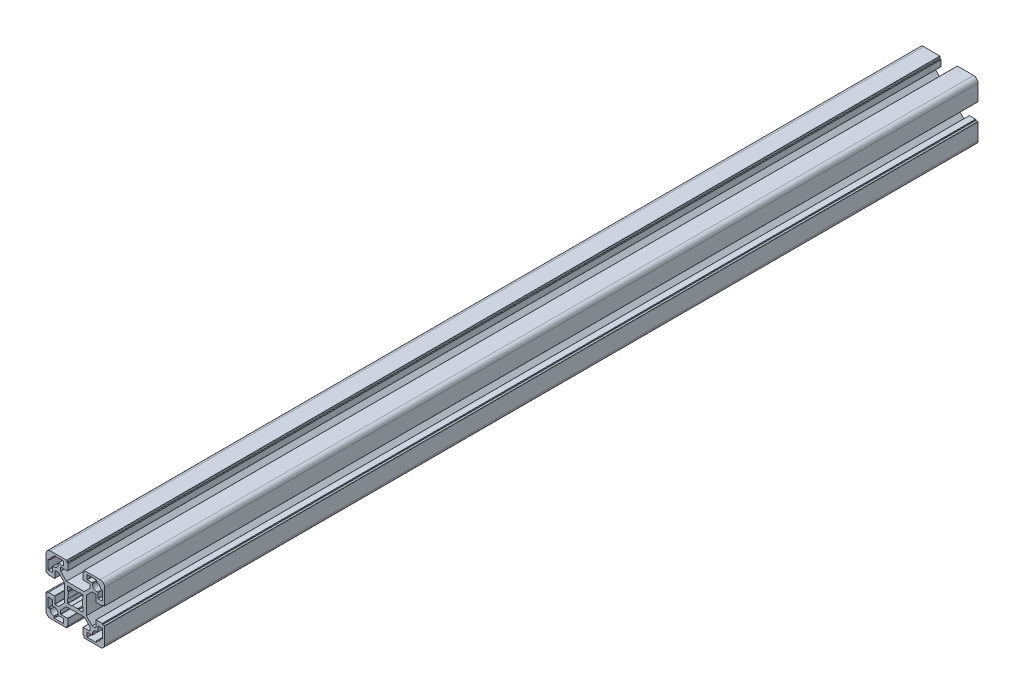
SolidWorks part; units mm, degrees
ref_plane "Спереди" through (0, 0, 0) normal (0, 0, 1) x (1, 0, 0)
ref_plane "Сверху" through (0, 0, 0) normal (0, 1, 0) x (1, 0, 0)
ref_plane "Справа" through (0, 0, 0) normal (1, 0, 0) x (0, 0, -1)
sketch "Model" plane through (0, 0, 0) normal (0, 0, 1) x (1, 0, 0)
  line L0 (15.7, -8) -> (18.3, -8)
  line L1 (18.5, -8.2) -> (18.5, -14.3)
  line L2 (18.3, -14.5) -> (17.4432, -14.5)
  line L3 (14.5, -17.4432) -> (14.5, -18.3)
  line L4 (14.3, -18.5) -> (8.2, -18.5)
  line L5 (8, -18.3) -> (8, -15.7)
  line L6 (8.2, -15.5) -> (11.55, -15.5)
  line L7 (11.75, -15.3) -> (11.75, -14.5)
  line L8 (14.5, -11.75) -> (15.3, -11.75)
  line L9 (15.5, -11.55) -> (15.5, -8.2)
  line L10 (-18.3, -8) -> (-15.7, -8)
  line L11 (-15.5, -8.2) -> (-15.5, -11.55)
  line L12 (-15.3, -11.75) -> (-14.5, -11.75)
  line L13 (-11.75, -14.5) -> (-11.75, -15.3)
  line L14 (-11.55, -15.5) -> (-8.2, -15.5)
  line L15 (-8, -15.7) -> (-8, -18.3)
  line L16 (-8.2, -18.5) -> (-14.3, -18.5)
  line L17 (-14.5, -18.3) -> (-14.5, -17.4432)
  line L18 (-17.4432, -14.5) -> (-18.3, -14.5)
  line L19 (-18.5, -14.3) -> (-18.5, -8.2)
  line L20 (-5, 5.2) -> (-2.261, 5.2)
  line L21 (-2.261, 5.2) -> (-2.0719, 4.7652)
  line L22 (2.0719, 4.7652) -> (2.261, 5.2)
  line L23 (2.261, 5.2) -> (5, 5.2)
  line L24 (5.2, 5) -> (5.2, 2.261)
  line L25 (5.2, 2.261) -> (4.7652, 2.0719)
  line L26 (4.7652, -2.0719) -> (5.2, -2.261)
  line L27 (5.2, -2.261) -> (5.2, -5)
  line L28 (5, -5.2) -> (2.261, -5.2)
  line L29 (2.261, -5.2) -> (2.0719, -4.7652)
  line L30 (-2.0719, -4.7652) -> (-2.261, -5.2)
  line L31 (-2.261, -5.2) -> (-5, -5.2)
  line L32 (-5.2, -5) -> (-5.2, -2.261)
  line L33 (-5.2, -2.261) -> (-4.7652, -2.0719)
  line L34 (-4.7652, 2.0719) -> (-5.2, 2.261)
  line L35 (-5.2, 2.261) -> (-5.2, 5)
  line L36 (11.55, 15.5) -> (8.2, 15.5)
  line L37 (8, 15.7) -> (8, 18.3)
  line L38 (8.2, 18.5) -> (14.3, 18.5)
  line L39 (14.5, 18.3) -> (14.5, 17.4432)
  line L40 (17.4432, 14.5) -> (18.3, 14.5)
  line L41 (18.5, 14.3) -> (18.5, 8.2)
  line L42 (18.3, 8) -> (15.7, 8)
  line L43 (15.5, 8.2) -> (15.5, 11.55)
  line L44 (15.3, 11.75) -> (14.5, 11.75)
  line L45 (11.75, 14.5) -> (11.75, 15.3)
  line L46 (-14.5, 11.75) -> (-15.3, 11.75)
  line L47 (-15.5, 11.55) -> (-15.5, 8.2)
  line L48 (-15.7, 8) -> (-18.3, 8)
  line L49 (-18.5, 8.2) -> (-18.5, 14.3)
  line L50 (-18.3, 14.5) -> (-17.4432, 14.5)
  line L51 (-14.5, 17.4432) -> (-14.5, 18.3)
  line L52 (-14.3, 18.5) -> (-8.2, 18.5)
  line L53 (-8, 18.3) -> (-8, 15.7)
  line L54 (-8.2, 15.5) -> (-11.55, 15.5)
  line L55 (-11.75, 15.3) -> (-11.75, 14.5)
  line L56 (7.5, 6.0858) -> (11.4642, 10.05)
  line L57 (11.4642, 10.05) -> (13.8, 10.05)
  line L58 (14, 9.85) -> (14, 5.35)
  line L59 (14.2, 5.15) -> (18.3, 5.15)
  line L60 (18.5, 5.35) -> (18.5, 5.6)
  line L61 (18.7, 5.8) -> (19.8, 5.8)
  line L62 (20, 6) -> (20, 17)
  line L63 (17, 20) -> (6, 20)
  line L64 (5.8, 19.8) -> (5.8, 18.7)
  line L65 (5.6, 18.5) -> (5.35, 18.5)
  line L66 (5.15, 18.3) -> (5.15, 14.2)
  line L67 (5.35, 14) -> (9.85, 14)
  line L68 (10.05, 13.8) -> (10.05, 11.4642)
  line L69 (10.05, 11.4642) -> (6.0858, 7.5)
  line L70 (6.0858, 7.5) -> (-6.0858, 7.5)
  line L71 (-6.0858, 7.5) -> (-10.05, 11.4642)
  line L72 (-10.05, 11.4642) -> (-10.05, 13.8)
  line L73 (-9.85, 14) -> (-5.35, 14)
  line L74 (-5.15, 14.2) -> (-5.15, 18.3)
  line L75 (-5.35, 18.5) -> (-5.6, 18.5)
  line L76 (-5.8, 18.7) -> (-5.8, 19.8)
  line L77 (-6, 20) -> (-17, 20)
  line L78 (-20, 17) -> (-20, 6)
  line L79 (-19.8, 5.8) -> (-18.7, 5.8)
  line L80 (-18.5, 5.6) -> (-18.5, 5.35)
  line L81 (-18.3, 5.15) -> (-14.2, 5.15)
  line L82 (-14, 5.35) -> (-14, 9.85)
  line L83 (-13.8, 10.05) -> (-11.4642, 10.05)
  line L84 (-11.4642, 10.05) -> (-7.5, 6.0858)
  line L85 (-7.5, 6.0858) -> (-7.5, -6.0858)
  line L86 (-7.5, -6.0858) -> (-11.4642, -10.05)
  line L87 (-11.4642, -10.05) -> (-13.8, -10.05)
  line L88 (-14, -9.85) -> (-14, -5.35)
  line L89 (-14.2, -5.15) -> (-18.3, -5.15)
  line L90 (-18.5, -5.35) -> (-18.5, -5.6)
  line L91 (-18.7, -5.8) -> (-19.8, -5.8)
  line L92 (-20, -6) -> (-20, -17)
  line L93 (-17, -20) -> (-6, -20)
  line L94 (-5.8, -19.8) -> (-5.8, -18.7)
  line L95 (-5.6, -18.5) -> (-5.35, -18.5)
  line L96 (-5.15, -18.3) -> (-5.15, -14.2)
  line L97 (-5.35, -14) -> (-9.85, -14)
  line L98 (-10.05, -13.8) -> (-10.05, -11.4642)
  line L99 (-10.05, -11.4642) -> (-6.0858, -7.5)
  line L100 (-6.0858, -7.5) -> (6.0858, -7.5)
  line L101 (6.0858, -7.5) -> (10.05, -11.4642)
  line L102 (10.05, -11.4642) -> (10.05, -13.8)
  line L103 (9.85, -14) -> (5.35, -14)
  line L104 (5.15, -14.2) -> (5.15, -18.3)
  line L105 (5.35, -18.5) -> (5.6, -18.5)
  line L106 (5.8, -18.7) -> (5.8, -19.8)
  line L107 (6, -20) -> (17, -20)
  line L108 (20, -17) -> (20, -6)
  line L109 (19.8, -5.8) -> (18.7, -5.8)
  line L110 (18.5, -5.6) -> (18.5, -5.35)
  line L111 (18.3, -5.15) -> (14.2, -5.15)
  line L112 (14, -5.35) -> (14, -9.85)
  line L113 (13.8, -10.05) -> (11.4642, -10.05)
  line L114 (11.4642, -10.05) -> (7.5, -6.0858)
  line L115 (7.5, -6.0858) -> (7.5, 6.0858)
  arc A0 (15.7, -8) -> (15.5, -8.2) centre (15.7, -8.2) ccw
  arc A1 (18.5, -8.2) -> (18.3, -8) centre (18.3, -8.2) ccw
  arc A2 (18.3, -14.5) -> (18.5, -14.3) centre (18.3, -14.3) ccw
  arc A3 (17.4432, -14.5) -> (17.2437, -14.6864) centre (17.4432, -14.7) ccw
  arc A4 (14.6864, -17.2437) -> (17.2437, -14.6864) centre (14.5, -14.5) ccw
  arc A5 (14.6864, -17.2437) -> (14.5, -17.4432) centre (14.7, -17.4432) ccw
  arc A6 (14.3, -18.5) -> (14.5, -18.3) centre (14.3, -18.3) ccw
  arc A7 (8, -18.3) -> (8.2, -18.5) centre (8.2, -18.3) ccw
  arc A8 (8.2, -15.5) -> (8, -15.7) centre (8.2, -15.7) ccw
  arc A9 (11.55, -15.5) -> (11.75, -15.3) centre (11.55, -15.3) ccw
  arc A10 (14.5, -11.75) -> (11.75, -14.5) centre (14.5, -14.5) ccw
  arc A11 (15.3, -11.75) -> (15.5, -11.55) centre (15.3, -11.55) ccw
  arc A12 (-18.3, -8) -> (-18.5, -8.2) centre (-18.3, -8.2) ccw
  arc A13 (-15.5, -8.2) -> (-15.7, -8) centre (-15.7, -8.2) ccw
  arc A14 (-15.5, -11.55) -> (-15.3, -11.75) centre (-15.3, -11.55) ccw
  arc A15 (-11.75, -14.5) -> (-14.5, -11.75) centre (-14.5, -14.5) ccw
  arc A16 (-11.75, -15.3) -> (-11.55, -15.5) centre (-11.55, -15.3) ccw
  arc A17 (-8, -15.7) -> (-8.2, -15.5) centre (-8.2, -15.7) ccw
  arc A18 (-8.2, -18.5) -> (-8, -18.3) centre (-8.2, -18.3) ccw
  arc A19 (-14.5, -18.3) -> (-14.3, -18.5) centre (-14.3, -18.3) ccw
  arc A20 (-14.5, -17.4432) -> (-14.6864, -17.2437) centre (-14.7, -17.4432) ccw
  arc A21 (-17.2437, -14.6864) -> (-14.6864, -17.2437) centre (-14.5, -14.5) ccw
  arc A22 (-17.2437, -14.6864) -> (-17.4432, -14.5) centre (-17.4432, -14.7) ccw
  arc A23 (-18.5, -14.3) -> (-18.3, -14.5) centre (-18.3, -14.3) ccw
  arc A24 (-5, 5.2) -> (-5.2, 5) centre (-5, 5) ccw
  arc A25 (-2.0719, 4.7652) -> (-1.8159, 4.6586) centre (-1.8885, 4.8449) ccw
  arc A26 (1.8159, 4.6586) -> (-1.8159, 4.6586) centre (0, 0) ccw
  arc A27 (1.8159, 4.6586) -> (2.0719, 4.7652) centre (1.8885, 4.8449) ccw
  arc A28 (5.2, 5) -> (5, 5.2) centre (5, 5) ccw
  arc A29 (4.7652, 2.0719) -> (4.6586, 1.8159) centre (4.8449, 1.8885) ccw
  arc A30 (4.6586, -1.8159) -> (4.6586, 1.8159) centre (0, 0) ccw
  arc A31 (4.6586, -1.8159) -> (4.7652, -2.0719) centre (4.8449, -1.8885) ccw
  arc A32 (5, -5.2) -> (5.2, -5) centre (5, -5) ccw
  arc A33 (2.0719, -4.7652) -> (1.8159, -4.6586) centre (1.8885, -4.8449) ccw
  arc A34 (-1.8159, -4.6586) -> (1.8159, -4.6586) centre (0, 0) ccw
  arc A35 (-1.8159, -4.6586) -> (-2.0719, -4.7652) centre (-1.8885, -4.8449) ccw
  arc A36 (-5.2, -5) -> (-5, -5.2) centre (-5, -5) ccw
  arc A37 (-4.7652, -2.0719) -> (-4.6586, -1.8159) centre (-4.8449, -1.8885) ccw
  arc A38 (-4.6586, 1.8159) -> (-4.6586, -1.8159) centre (0, 0) ccw
  arc A39 (-4.6586, 1.8159) -> (-4.7652, 2.0719) centre (-4.8449, 1.8885) ccw
  arc A40 (11.75, 15.3) -> (11.55, 15.5) centre (11.55, 15.3) ccw
  arc A41 (8, 15.7) -> (8.2, 15.5) centre (8.2, 15.7) ccw
  arc A42 (8.2, 18.5) -> (8, 18.3) centre (8.2, 18.3) ccw
  arc A43 (14.5, 18.3) -> (14.3, 18.5) centre (14.3, 18.3) ccw
  arc A44 (14.5, 17.4432) -> (14.6864, 17.2437) centre (14.7, 17.4432) ccw
  arc A45 (17.2437, 14.6864) -> (14.6864, 17.2437) centre (14.5, 14.5) ccw
  arc A46 (17.2437, 14.6864) -> (17.4432, 14.5) centre (17.4432, 14.7) ccw
  arc A47 (18.5, 14.3) -> (18.3, 14.5) centre (18.3, 14.3) ccw
  arc A48 (18.3, 8) -> (18.5, 8.2) centre (18.3, 8.2) ccw
  arc A49 (15.5, 8.2) -> (15.7, 8) centre (15.7, 8.2) ccw
  arc A50 (15.5, 11.55) -> (15.3, 11.75) centre (15.3, 11.55) ccw
  arc A51 (11.75, 14.5) -> (14.5, 11.75) centre (14.5, 14.5) ccw
  arc A52 (-14.5, 11.75) -> (-11.75, 14.5) centre (-14.5, 14.5) ccw
  arc A53 (-15.3, 11.75) -> (-15.5, 11.55) centre (-15.3, 11.55) ccw
  arc A54 (-15.7, 8) -> (-15.5, 8.2) centre (-15.7, 8.2) ccw
  arc A55 (-18.5, 8.2) -> (-18.3, 8) centre (-18.3, 8.2) ccw
  arc A56 (-18.3, 14.5) -> (-18.5, 14.3) centre (-18.3, 14.3) ccw
  arc A57 (-17.4432, 14.5) -> (-17.2437, 14.6864) centre (-17.4432, 14.7) ccw
  arc A58 (-14.6864, 17.2437) -> (-17.2437, 14.6864) centre (-14.5, 14.5) ccw
  arc A59 (-14.6864, 17.2437) -> (-14.5, 17.4432) centre (-14.7, 17.4432) ccw
  arc A60 (-14.3, 18.5) -> (-14.5, 18.3) centre (-14.3, 18.3) ccw
  arc A61 (-8, 18.3) -> (-8.2, 18.5) centre (-8.2, 18.3) ccw
  arc A62 (-8.2, 15.5) -> (-8, 15.7) centre (-8.2, 15.7) ccw
  arc A63 (-11.55, 15.5) -> (-11.75, 15.3) centre (-11.55, 15.3) ccw
  arc A64 (14, 9.85) -> (13.8, 10.05) centre (13.8, 9.85) ccw
  arc A65 (14, 5.35) -> (14.2, 5.15) centre (14.2, 5.35) ccw
  arc A66 (18.3, 5.15) -> (18.5, 5.35) centre (18.3, 5.35) ccw
  arc A67 (18.7, 5.8) -> (18.5, 5.6) centre (18.7, 5.6) ccw
  arc A68 (19.8, 5.8) -> (20, 6) centre (19.8, 6) ccw
  arc A69 (20, 17) -> (17, 20) centre (17, 17) ccw
  arc A70 (6, 20) -> (5.8, 19.8) centre (6, 19.8) ccw
  arc A71 (5.6, 18.5) -> (5.8, 18.7) centre (5.6, 18.7) ccw
  arc A72 (5.35, 18.5) -> (5.15, 18.3) centre (5.35, 18.3) ccw
  arc A73 (5.15, 14.2) -> (5.35, 14) centre (5.35, 14.2) ccw
  arc A74 (10.05, 13.8) -> (9.85, 14) centre (9.85, 13.8) ccw
  arc A75 (-9.85, 14) -> (-10.05, 13.8) centre (-9.85, 13.8) ccw
  arc A76 (-5.35, 14) -> (-5.15, 14.2) centre (-5.35, 14.2) ccw
  arc A77 (-5.15, 18.3) -> (-5.35, 18.5) centre (-5.35, 18.3) ccw
  arc A78 (-5.8, 18.7) -> (-5.6, 18.5) centre (-5.6, 18.7) ccw
  arc A79 (-5.8, 19.8) -> (-6, 20) centre (-6, 19.8) ccw
  arc A80 (-17, 20) -> (-20, 17) centre (-17, 17) ccw
  arc A81 (-20, 6) -> (-19.8, 5.8) centre (-19.8, 6) ccw
  arc A82 (-18.5, 5.6) -> (-18.7, 5.8) centre (-18.7, 5.6) ccw
  arc A83 (-18.5, 5.35) -> (-18.3, 5.15) centre (-18.3, 5.35) ccw
  arc A84 (-14.2, 5.15) -> (-14, 5.35) centre (-14.2, 5.35) ccw
  arc A85 (-13.8, 10.05) -> (-14, 9.85) centre (-13.8, 9.85) ccw
  arc A86 (-14, -9.85) -> (-13.8, -10.05) centre (-13.8, -9.85) ccw
  arc A87 (-14, -5.35) -> (-14.2, -5.15) centre (-14.2, -5.35) ccw
  arc A88 (-18.3, -5.15) -> (-18.5, -5.35) centre (-18.3, -5.35) ccw
  arc A89 (-18.7, -5.8) -> (-18.5, -5.6) centre (-18.7, -5.6) ccw
  arc A90 (-19.8, -5.8) -> (-20, -6) centre (-19.8, -6) ccw
  arc A91 (-20, -17) -> (-17, -20) centre (-17, -17) ccw
  arc A92 (-6, -20) -> (-5.8, -19.8) centre (-6, -19.8) ccw
  arc A93 (-5.6, -18.5) -> (-5.8, -18.7) centre (-5.6, -18.7) ccw
  arc A94 (-5.35, -18.5) -> (-5.15, -18.3) centre (-5.35, -18.3) ccw
  arc A95 (-5.15, -14.2) -> (-5.35, -14) centre (-5.35, -14.2) ccw
  arc A96 (-10.05, -13.8) -> (-9.85, -14) centre (-9.85, -13.8) ccw
  arc A97 (9.85, -14) -> (10.05, -13.8) centre (9.85, -13.8) ccw
  arc A98 (5.35, -14) -> (5.15, -14.2) centre (5.35, -14.2) ccw
  arc A99 (5.15, -18.3) -> (5.35, -18.5) centre (5.35, -18.3) ccw
  arc A100 (5.8, -18.7) -> (5.6, -18.5) centre (5.6, -18.7) ccw
  arc A101 (5.8, -19.8) -> (6, -20) centre (6, -19.8) ccw
  arc A102 (17, -20) -> (20, -17) centre (17, -17) ccw
  arc A103 (20, -6) -> (19.8, -5.8) centre (19.8, -6) ccw
  arc A104 (18.5, -5.6) -> (18.7, -5.8) centre (18.7, -5.6) ccw
  arc A105 (18.5, -5.35) -> (18.3, -5.15) centre (18.3, -5.35) ccw
  arc A106 (14.2, -5.15) -> (14, -5.35) centre (14.2, -5.35) ccw
  arc A107 (13.8, -10.05) -> (14, -9.85) centre (13.8, -9.85) ccw
  dimension "D1" = 40
extrude "Бобышка-Вытянуть1" add sketch "Model" against normal mid plane 596
